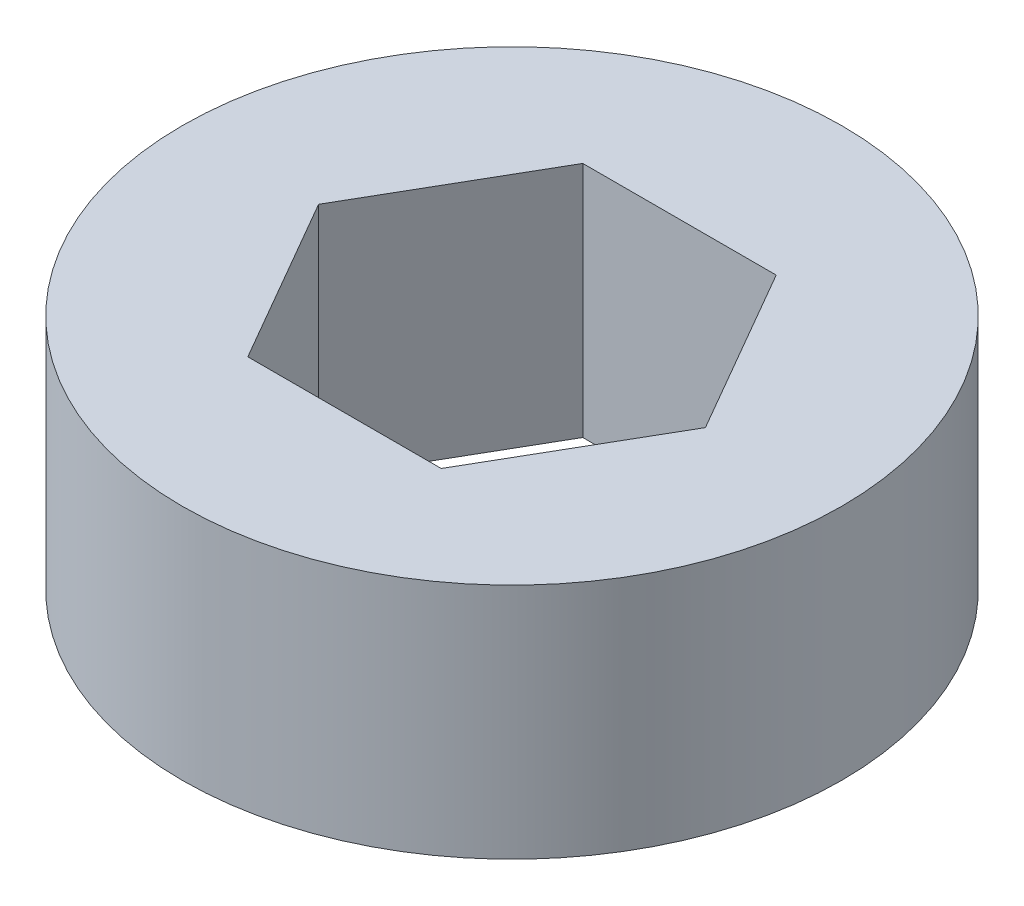
SolidWorks part; units mm, degrees
ref_plane "Alzado" through (0, 0, 0) normal (0, 0, 1) x (1, 0, 0)
ref_plane "Planta" through (0, 0, 0) normal (0, 1, 0) x (1, 0, 0)
ref_plane "Vista lateral" through (0, 0, 0) normal (1, 0, 0) x (0, 0, -1)
sketch "Croquis1" plane through (0, 0, 0) normal (0, 1, 0) x (1, 0, 0)
  line L1 (7.3323, 0) -> (3.6662, 6.35)
  line L2 (3.6662, 6.35) -> (-3.6662, 6.35)
  line L3 (-3.6662, 6.35) -> (-7.3323, 0)
  line L4 (-7.3323, 0) -> (-3.6662, -6.35)
  line L5 (-3.6662, -6.35) -> (3.6662, -6.35)
  line L6 (3.6662, -6.35) -> (7.3323, 0)
  circle A0 centre (0, 0) radius 12.5
  circle A1 centre (0, 0) radius 6.35 construction
  dimension "D2" = 25
  dimension "D1" = 12.7
extrude "Saliente-Extruir1" add sketch "Croquis1" along normal blind 9
